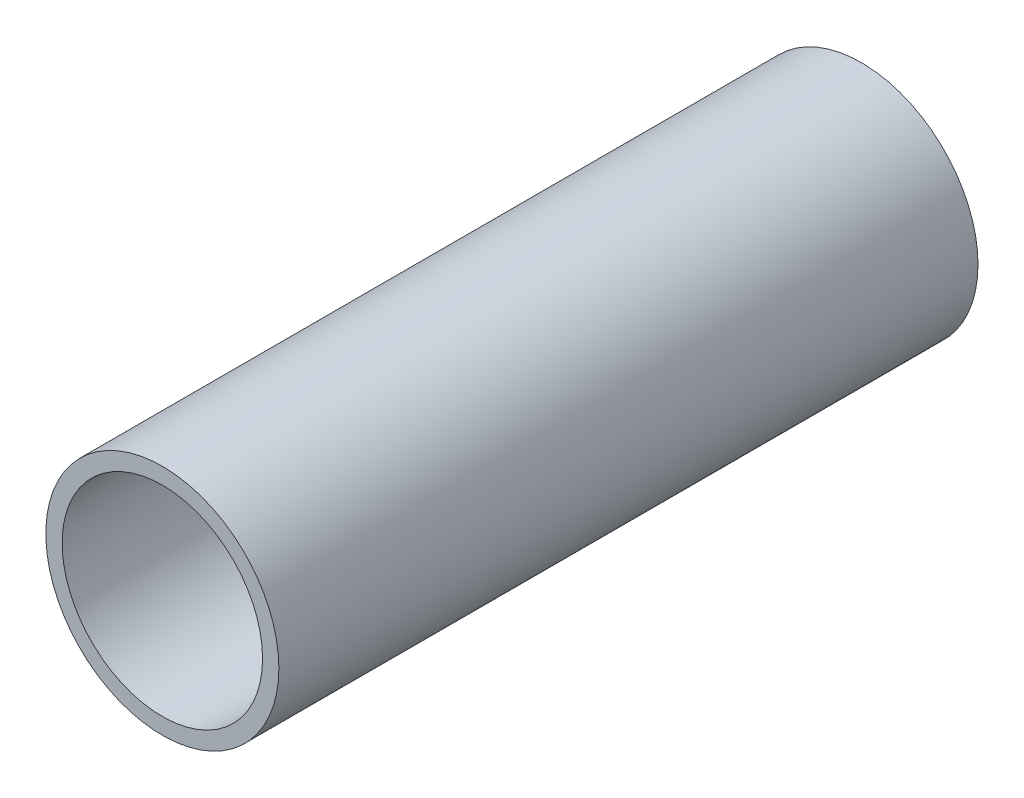
SolidWorks part; units mm, degrees
material "6061 Alloy"
ref_plane "Front" through (0, 0, 0) normal (0, 0, 1) x (1, 0, 0)
ref_plane "Top" through (0, 0, 0) normal (0, 1, 0) x (1, 0, 0)
ref_plane "Right" through (0, 0, 0) normal (1, 0, 0) x (0, 0, -1)
sketch "Sketch1" plane through (0, 0, 0) normal (0, 0, 1) x (1, 0, 0)
  circle A0 centre (0, 0) radius 6.35
  circle A1 centre (0, 0) radius 5.461
extrude "Extrude1" add sketch "Sketch1" along normal blind 38.1
sketch "Sketch2" plane through (0, 0, 0) normal (0, 1, 0) x (1, 0, 0)
  line L0 (0, 0) -> (0, -9.525)
  line L1 (0, -38.1) -> (0, -28.575)
  line L2 (-6.35, -38.1) -> (6.35, -38.1) construction
  circle A0 centre (0, -9.525) radius 2
  circle A1 centre (0, -28.575) radius 2
extrude "Cut-Extrude1" cut sketch "Sketch2" against normal blind 10 contours A0 | A1
